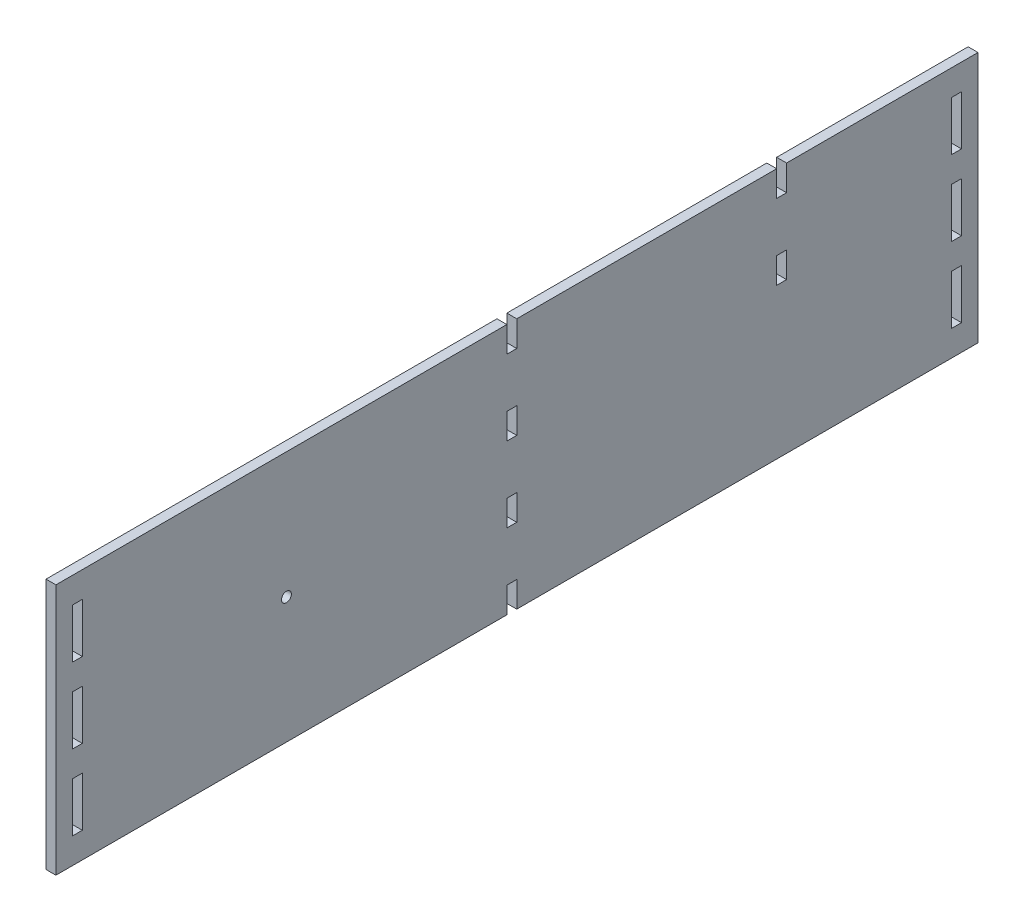
SolidWorks part; units mm, degrees
material "ENPH 253 Hardboard"
ref_plane "Front Plane" through (0, 0, 0) normal (0, 0, 1) x (1, 0, 0)
ref_plane "Top Plane" through (0, 0, 0) normal (0, 1, 0) x (1, 0, 0)
ref_plane "Right Plane" through (0, 0, 0) normal (1, 0, 0) x (0, 0, -1)
sketch "Sketch1" plane through (0, 0, 0) normal (1, 0, 0) x (0, 0, -1)
  line L1 (-139.7, 38.1) -> (139.7, 38.1)
  line L2 (-139.7, 38.1) -> (-139.7, -38.1)
  line L3 (-139.7, -38.1) -> (139.7, -38.1)
  line L4 (139.7, 38.1) -> (139.7, -38.1)
  line L5 (-139.7, 38.1) -> (139.7, -38.1) construction
  line L6 (-139.7, -38.1) -> (139.7, 38.1) construction
  point P0 (0, 0)
  dimension "D1" = 279.4
  dimension "D2" = 76.2
extrude "Boss-Extrude1" add sketch "Sketch1" against normal blind 3 contours L2 L3 L4 L1
sketch "Sketch3" plane through (-3, 0, 0) normal (-1, 0, 0) x (0, 0, 1)
  line L0 (-139.7, 38.1) -> (-139.7, -38.1) construction
  line L1 (139.7, 38.1) -> (139.7, -38.1) construction
  line L2 (139.7, 38.1) -> (-139.7, 38.1) construction
  line L3 (134.7, 30.3) -> (131.7, 30.3)
  line L4 (134.7, 30.3) -> (134.7, 15.3)
  line L5 (134.7, 15.3) -> (131.7, 15.3)
  line L6 (131.7, 30.3) -> (131.7, 15.3)
  line L7 (139.7, 38.1) -> (139.7, -38.1) construction
  circle A0 centre (69.85, 0) radius 50.8 construction
  circle A1 centre (-69.85, 0) radius 50.8 construction
  dimension "D1" = 101.6
  dimension "D2" = 101.6
  dimension "D3" = 69.85
  dimension "D4" = 69.85
  dimension "D5" = 15
  dimension "D6" = 7.8
  dimension "D7" = 5
  dimension "D8" = 3
extrude "Cut-Extrude1" cut sketch "Sketch3" against normal through all
pattern_linear "LPattern1" count 3 spacing 22.8 along (0, -1, 0) of "Cut-Extrude1"
mirror "Mirror1" about plane through (0, 0, 0) normal (0, 0, 1) of "LPattern1", "Cut-Extrude1"
hole_wizard "Ø3.0mm Clearance Dowel Hole1" positions "Sketch4" profile "Sketch5" hole size "Ø3.0" standard "ANSI Metric" end condition through all
sketch "Sketch4" plane through (-3, 0, 0) normal (-1, 0, 0) x (0, 0, 1)
  point P3 (69.85, 0)
  point P6 (0, 0)
sketch "Sketch5" plane through (-3, 0, 69.85) normal (0, 1, 0) x (0, 0, 1)
  line L0 (0, 0) -> (0, 3)
  line L1 (0, 3) -> (1.5, 3)
  line L2 (1.5, 3) -> (1.5, 0)
  line L5 (1.5, 0) -> (0, 0)
  line L11 (0, -6.35) -> (0, 107.95) construction
  dimension "Thru Hole Dia." = 3
  dimension "Thru Hole Depth" = 3
sketch "Sketch6" plane through (-3, 0, 0) normal (-1, 0, 0) x (0, 0, 1)
  line L0 (139.7, 38.1) -> (-139.7, 38.1) construction
  line L1 (0.06, 38.1) -> (3.06, 38.1)
  line L2 (0.06, 38.1) -> (0.06, 30.3)
  line L3 (0.06, 30.3) -> (3.06, 30.3)
  line L4 (3.06, 38.1) -> (3.06, 30.3)
  dimension "D1" = 136.64
  dimension "D2" = 3
  dimension "D3" = 7.8
extrude "Cut-Extrude2" cut sketch "Sketch6" against normal through all
pattern_linear "LPattern2" count 4 spacing 22.8 along (0, -1, 0) of "Cut-Extrude2"
sketch "Sketch7" plane through (-3, 0, 0) normal (-1, 0, 0) x (0, 0, 1)
  line L0 (139.7, 38.1) -> (3.06, 38.1) construction
  line L1 (-81.7, 38.1) -> (-78.7, 38.1)
  line L2 (-81.7, 38.1) -> (-81.7, 30.3)
  line L3 (-81.7, 30.3) -> (-78.7, 30.3)
  line L4 (-78.7, 38.1) -> (-78.7, 30.3)
  dimension "D1" = 3
  dimension "D2" = 7.8
  dimension "D3" = 50
extrude "Cut-Extrude3" cut sketch "Sketch7" against normal blind 10
pattern_linear "LPattern3" count 2 spacing 22.8 along (0, -1, 0) of "Cut-Extrude3"
equation "\"D4@Sketch3\"=\"D3@Sketch3\""
